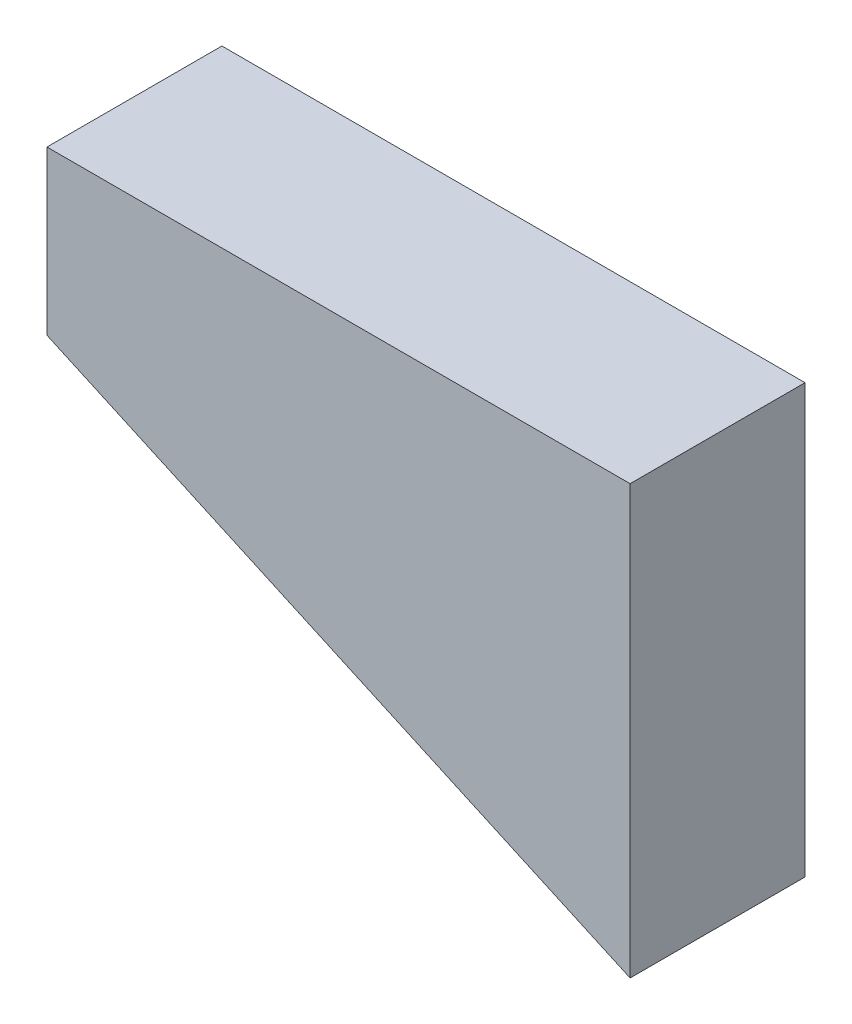
SolidWorks part; units mm, degrees
material "Pine"
ref_plane "Front Plane" through (0, 0, 0) normal (0, 0, 1) x (1, 0, 0)
ref_plane "Top Plane" through (0, 0, 0) normal (0, 1, 0) x (1, 0, 0)
ref_plane "Right Plane" through (0, 0, 0) normal (1, 0, 0) x (0, 0, -1)
sketch "Sketch1" plane through (0, 0, 0) normal (0, 0, 1) x (1, 0, 0)
  line L33 (-673.6845, 1780.4468) -> (-737.1845, 1780.4468)
  line L35 (-737.1845, 1762.6932) -> (-673.6845, 1733.8295)
  line L63 (-737.1845, 1780.4468) -> (-737.1845, 1762.6932)
  line L67 (-673.6845, 1780.4468) -> (-673.6845, 1733.8295)
  line L68 (-673.6845, 1780.4468) -> (-673.6845, 1762.6932) construction
extrude "Boss-Extrude1" add sketch "Sketch1" along normal blind 19.05 contours L67 L33 L63 L35
